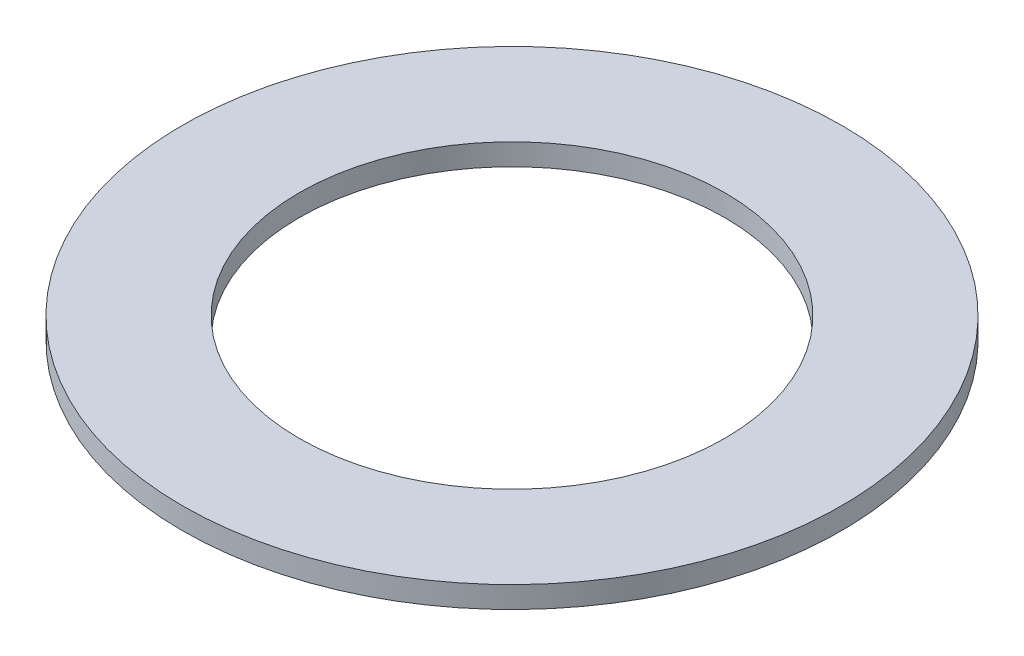
SolidWorks part; units mm, degrees
material "1060 Alloy"
ref_plane "Front Plane" through (0, 0, 0) normal (0, 0, 1) x (1, 0, 0)
ref_plane "Top Plane" through (0, 0, 0) normal (0, 1, 0) x (1, 0, 0)
ref_plane "Right Plane" through (0, 0, 0) normal (1, 0, 0) x (0, 0, -1)
sketch "Sketch1" plane through (0, 0, 0) normal (0, 1, 0) x (1, 0, 0)
  circle A0 centre (0, 0) radius 76.2
  circle A1 centre (0, 0) radius 49.2
  circle A2 centre (0, 0) radius 76.2 construction
  dimension "D1" = 152.4
  dimension "D2" = 98.4
  dimension "D3" = 152.4
extrude "Boss-Extrude1" add sketch "Sketch1" along normal blind 5
